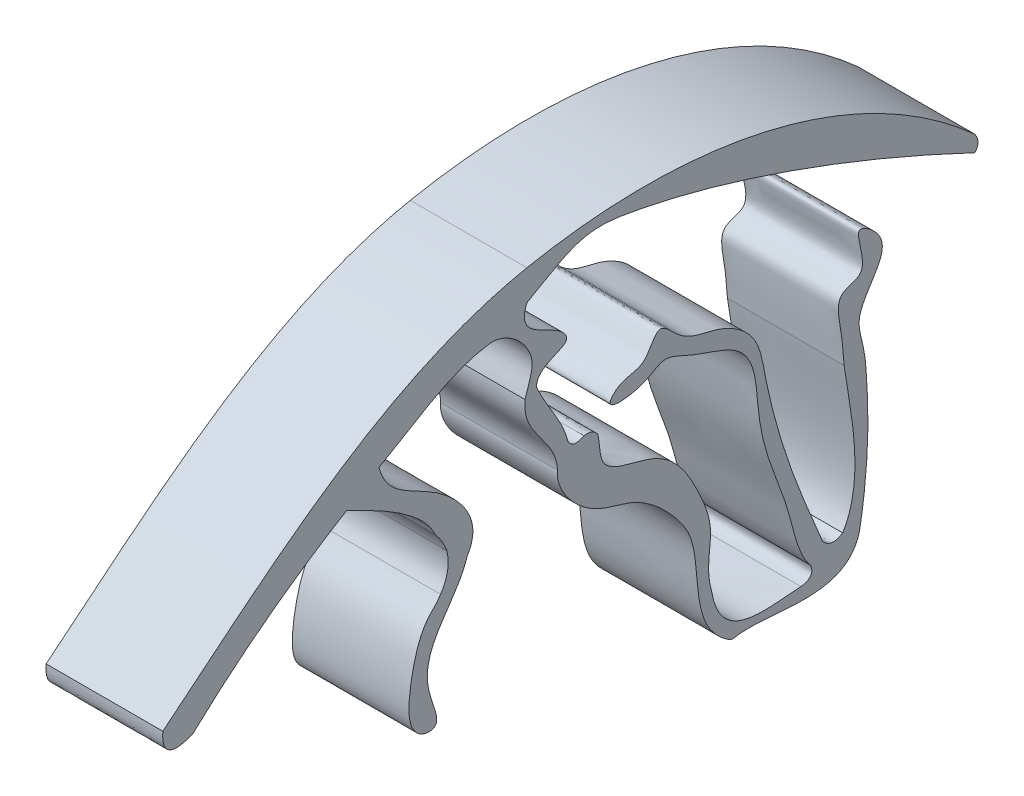
SolidWorks part; units mm, degrees
ref_plane "Front Plane" through (0, 0, 0) normal (0, 0, 1) x (1, 0, 0)
ref_plane "Top Plane" through (0, 0, 0) normal (0, 1, 0) x (1, 0, 0)
ref_plane "Right Plane" through (0, 0, 0) normal (1, 0, 0) x (0, 0, -1)
sketch "Sketch1" plane through (0, 0, 0) normal (1, 0, 0) x (0, 0, -1)
  line L0 (-5.7285, 63.9527) -> (142.5922, 116.011) construction
  spline S0 degree 3 poles (-3.536, 20.2882) (10.0338, 22.9617) (24.4194, 20.401) (34.8511, 11.0027) knots 0.473952 0.473952 0.473952 0.473952 1 1 1 1
  spline S1 degree 2 poles (-32.1844, 0) (-26.2428, 5.5978) (-18.9722, 10.0026) knots 0 0 0 0.556812 0.556812 0.556812
  spline S2 degree 3 poles (34.8511, 9.6274) (28.6552, 12.5696) (18.811, 16.6279) (7.7635, 19.5917) (1.018, 20.6713) (-1.7714, 18.6591) (-3.5358, 17.695) knots 0 0 0 0 0.479063 0.707397 0.794305 0.928423 0.928423 0.928423 0.928423
  spline S3 degree 3 poles (-3.5358, 17.695) (-4.5296, 15.3469) (-1.1459, 15.0998) (0.4832, 12.7185) (-2.7552, 12.3586) (-2.7086, 11.0027) knots 0 0 0 0 0.202924 0.262155 0.36668 0.36668 0.36668 0.36668
  spline S4 degree 3 poles (-11.3955, 4.4253) (-12.6384, 7.0583) (-16.7829, 8.8694) (-18.9722, 10.0026) knots 0.545737 0.545737 0.545737 0.545737 1 1 1 1
  spline S5 degree 3 poles (-16.2184, 11.8062) (-15.5553, 9.2287) (-11.4886, 8.5096) (-7.4954, 4.0296) (-8.456, 1.7557) (-8.6301, 1.4891) knots 0 0 0 0 0.374967 0.716088 0.771729 0.771729 0.771729 0.771729
  spline S6 degree 3 poles (25.5391, -2.0013) (25.5266, -1.5719) (25.3131, 0.4739) (24.5084, 2.0957) (26.1344, 4.674) (27.7424, 7.17) (23.7811, 10.0512) (26.2255, 5.2387) (22.7698, 5.1304) (23.4755, 2.0081) (23.5735, 0.4051) (23.6494, -0.5705) knots 0.103533 0.103533 0.103533 0.103533 0.137225 0.252241 0.335792 0.453099 0.531649 0.649934 0.71225 0.803022 0.912855 0.912855 0.912855 0.912855
  spline S7 degree 2 poles (20.7713, -13.9442) (21.1962, -14.9429) (19.9493, -15.1199) knots 0 0 0 1 1 1
  spline S8 degree 3 poles (12.2827, -11.6021) (11.717, -9.6859) (12.6852, -7.3245) (10.9582, -3.0722) (8.5871, 1.2512) (2.4498, 1.4724) (2.7313, 4.2738) (2.5094, 4.9435) knots 0 0 0 0 0.083394 0.137742 0.243698 0.320986 0.36489 0.36489 0.36489 0.36489
  spline S9 degree 2 poles (-34.739, 1.4891) (-34.9287, -1.085) (-32.1844, 0) knots 0 0 0 1 1 1
  spline S10 degree 2 poles (34.8511, 11.0027) (35.3864, 10.2291) (34.8511, 9.6274) knots 0 0 0 1 1 1
  spline S11 degree 3 poles (25.5391, -2.0013) (25.8519, -5.8607) (25.6632, -9.6834) (24.9731, -13.4694) knots 0.10118 0.10118 0.10118 0.10118 1 1 1 1
  spline S12 degree 3 poles (23.6494, -0.5705) (24.0389, -3.6624) (25.5982, -9.64) (23.5233, -12.9205) knots 0 0 0 0 0.825093 0.825093 0.825093 0.825093
  spline S13 degree 3 poles (-34.739, 1.4891) (-25.3894, 9.098) (-15.8328, 17.8393) (-3.5358, 20.2883) knots 0 0 0 0 1 1 1 1
  spline S14 degree 3 poles (14.1308, -16.0776) (17.0097, -15.407) (23.8631, -17.9738) (24.9731, -13.4694) knots 0 0 0 0 1 1 1 1
  spline S15 degree 3 poles (12.2827, -11.6021) (13.0563, -16.3545) (17.0627, -15.2422) (19.9493, -15.1199) knots 0 0 0 0 0.60965 0.60965 0.60965 0.60965
  spline S16 degree 3 poles (-16.2184, 11.8062) (-12.9776, 13.6069) (-10.3316, 15.6791) (-6.9389, 16.2181) knots 0.635291 0.635291 0.635291 0.635291 1 1 1 1
  spline S17 degree 2 poles (23.5233, -12.9205) (22.5851, -13.5523) (21.8035, -12.7012) knots 0 0 0 1 1 1
  spline S18 degree 3 poles (1.357, 5.3701) (0.5636, 5.0109) (0.218, 5.2096) (0, 5.6071) knots 0.064159 0.064159 0.064159 0.064159 0.436711 0.436711 0.436711 0.436711
  spline S19 degree 3 poles (21.8035, -12.7012) (21.5104, -11.9793) (20.087, -8.61) (18.5489, -4.6366) (16.999, 0.8895) (16.3281, 5.5665) (13.0629, 7.8416) (9.8851, 7.9448) (7.6773, 10.9061) (6.6626, 7.6871) (4.6769, 8.0834) (2.784, 6.0609) (6.5283, 6.4149) (8.2632, 8.0006) (10.5411, 6.5512) (16.1298, 5.2018) (16.0502, -0.0889) (17.0803, -4.373) (19.002, -8.8235) (19.7518, -12.8452) (20.7713, -13.9442) knots 0.043284 0.043284 0.043284 0.043284 0.070188 0.157912 0.259538 0.309962 0.369972 0.421258 0.450241 0.480238 0.514104 0.528943 0.570491 0.596433 0.632482 0.677832 0.763885 0.843045 0.900045 0.955274 0.955274 0.955274 0.955274
  spline S20 degree 3 poles (-0.9223, 3.9434) (-0.997, 6.5501) (-4.0125, 7.7665) (-3.6987, 10.5829) knots 0 0 0 0 1 1 1 1
  spline S21 degree 3 poles (-3.6987, 10.5829) (-3.3887, 11.6778) (-2.2576, 13.6528) (-5.2849, 16.574) (-6.9389, 16.2181) knots 0.684063 0.684063 0.684063 0.684063 0.804598 1 1 1 1
  spline S22 degree 3 poles (-0.9223, 3.9434) (-0.989, 3.466) (-0.4798, 1.5724) (2.2686, -0.9609) (6.1959, -1.4364) (10.151, -5.3975) (11.0185, -7.9389) (11.181, -14.1198) (13.742, -16.0562) (14.1308, -16.0776) knots 0.440867 0.440867 0.440867 0.440867 0.467019 0.535882 0.597258 0.688484 0.789269 0.864222 0.912566 0.912566 0.912566 0.912566
  spline S23 degree 2 poles (2.5094, 4.9435) (2.03, 5.5112) (1.357, 5.3701) knots 0 0 0 1 1 1
  spline S24 degree 3 poles (0, 5.6071) (-0.5105, 7.6047) (-1.9224, 9.1428) (-2.7086, 11.0027) knots 0 0 0 0 1 1 1 1
  spline S25 degree 3 poles (-8.6301, 1.4891) (-9.5705, -1.5271) (-13.6421, -3.9122) (-10.7464, -9.8641) (-12.5589, -10.1167) (-13.8877, -8.678) (-13.4457, -4.7795) (-12.5363, -1.7646) (-11.2394, -0.7356) (-10.9397, -0.247) knots 0 0 0 0 0.334756 0.434438 0.507607 0.625275 0.748217 0.885474 0.947565 0.947565 0.947565 0.947565
  spline S26 degree 2 poles (-10.3977, 2.7203) (-10.6553, 3.5069) (-11.3955, 4.4253) knots 0.955385 0.955385 0.955385 1 1 1
  spline S27 degree 2 poles (-10.3977, 2.7203) (-10.0158, 1.1153) (-10.9397, -0.247) knots 0 0 0 1 1 1
  point P0 (0, 0)
extrude "Boss-Extrude1" add sketch "Sketch1" along normal blind 10 contours S26 S27 S25 S5 S16 S21 S20 S22 S14 S11 S6 S12 S17 S19 S7 S15 S8 S23 S18 S24 S3 S2 S10 S0 S13 S9 S1 S4
